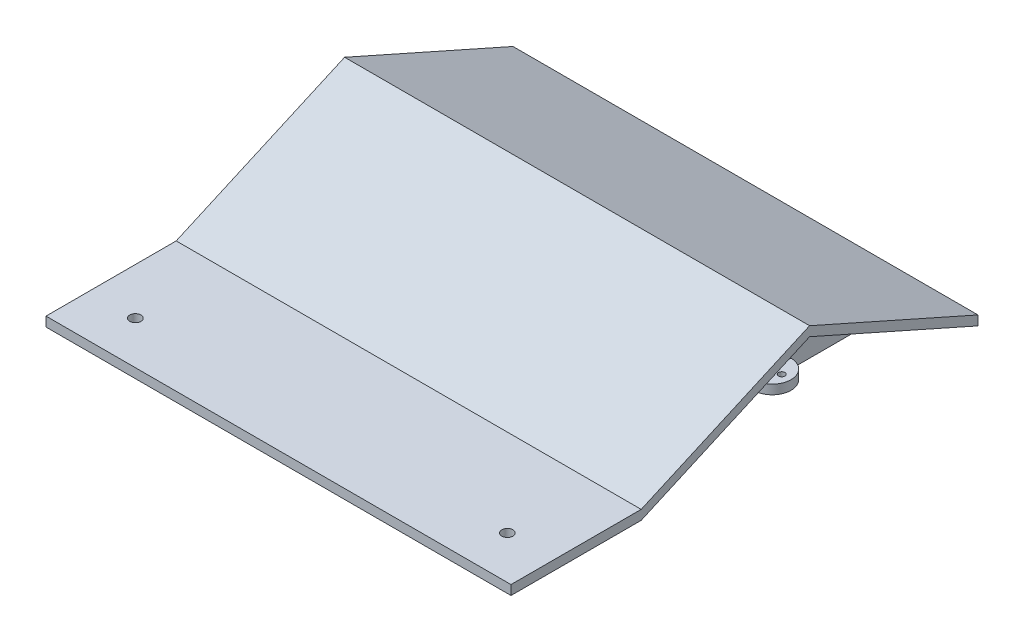
SolidWorks part; units mm, degrees
ref_plane "Front Plane" through (0, 0, 0) normal (0, 0, 1) x (1, 0, 0)
ref_plane "Top Plane" through (0, 0, 0) normal (0, 1, 0) x (1, 0, 0)
ref_plane "Right Plane" through (0, 0, 0) normal (1, 0, 0) x (0, 0, -1)
sketch "Sketch1" plane through (0, 0, 0) normal (1, 0, 0) x (0, 0, -1)
  line L0 (0, 0) -> (135, 0)
  line L1 (67.5, 0) -> (67.5, 30)
  line L2 (67.5, 30) -> (135, 0)
  line L3 (135, 0) -> (158.0421, -10.2409)
  line L4 (158.0421, -10.2409) -> (158.0421, -5.1205)
  line L5 (158.0421, -5.1205) -> (67.5, 35.1205)
  line L6 (67.5, 30) -> (0, 0)
  line L7 (0, 0) -> (-23.0421, -10.2409)
  line L8 (-23.0421, -10.2409) -> (-23.0421, -5.1205)
  line L9 (-23.0421, -5.1205) -> (67.5, 35.1205)
extrude "Boss-Extrude1" add sketch "Sketch1" against normal blind 250 contours L9 L8 L7 L6 L2 L3 L4 L5
sketch "Sketch2" plane through (0, 0, 0) normal (1, 0, 0) x (0, 0, -1)
  line L0 (0, 0) -> (135, 0)
  line L1 (67.5, 30) -> (158.0421, -10.2409) construction
  line L2 (135, 0) -> (67.5, 30)
  line L3 (67.5, 30) -> (0, 0)
extrude "Boss-Extrude2" add sketch "Sketch2" against normal blind 25
sketch "Sketch3" plane through (0, 0, 0) normal (1, 0, 0) x (0, 0, -1)
  line L0 (0, 0) -> (135, 0)
  line L1 (135, 0) -> (67.5, 30)
  line L2 (67.5, 30) -> (0, 0)
extrude "Cut-Extrude1" cut sketch "Sketch3" against normal blind 20
sketch "Sketch4" plane through (-250, 0, 0) normal (-1, 0, 0) x (0, 0, 1)
  line L0 (-135, 0) -> (0, 0)
  line L1 (0, 0) -> (-67.5, 30)
  line L2 (-67.5, 30) -> (-135, 0)
extrude "Boss-Extrude3" add sketch "Sketch4" against normal blind 25
sketch "Sketch5" plane through (-250, 0, 0) normal (-1, 0, 0) x (0, 0, 1)
  line L0 (-135, 0) -> (0, 0)
  line L1 (0, 0) -> (-67.5, 29.5827)
  line L2 (-67.5, 29.5827) -> (-135, 0)
extrude "Cut-Extrude2" cut sketch "Sketch5" against normal blind 20
sketch "Sketch6" plane through (0, 0, 0) normal (0, -1, 0) x (-1, 0, 0)
  line L0 (230, 67.5) -> (240, 67.5)
  circle A0 centre (230, 67.5) radius 10
  circle A1 centre (235, 67.5) radius 1.7
  line M1 (230, 0) -> (230, 135)
  line M3 (225, 135) -> (225, 0)
extrude "Boss-Extrude4" add sketch "Sketch6" against normal blind 5 contours A1 L0 A0 M1 | A1 L0 A0 M1 | A0 M3 | A0 M1 M3
sketch "Sketch7" plane through (0, 0, 0) normal (0, -1, 0) x (-1, 0, 0)
  line L0 (20, 67.5) -> (10, 67.5)
  circle A0 centre (20, 67.5) radius 10
  circle A1 centre (15, 67.5) radius 1.7
  line M1 (20, 135) -> (20, 0)
  line M3 (25, 0) -> (25, 135)
extrude "Boss-Extrude5" add sketch "Sketch7" against normal blind 5 contours A1 L0 A0 M1 | A1 L0 A0 M1 | A0 M1 M3 | A0 M3
sketch "Sketch8" plane through (-230, 0, 0) normal (-1, 0, 0) x (0, 0, 1)
  line L0 (-67.5, 5) -> (-67.5, 25)
  line L1 (-57.5, 5) -> (-77.5, 5) construction
  circle A0 centre (-67.5, 25) radius 1.5
extrude "Cut-Extrude3" cut sketch "Sketch8" against normal blind 10
sketch "Sketch9" plane through (-250, 0, 0) normal (-1, 0, 0) x (0, 0, 1)
  line L0 (23.0421, -5.1205) -> (93.0421, -5.1205)
  line L1 (93.0421, -5.1205) -> (93.0421, -10.2409)
  line L2 (93.0421, -10.2409) -> (23.0421, -10.2409)
  line L3 (23.0421, -10.2409) -> (23.0421, -5.1205)
extrude "Boss-Extrude7" add sketch "Sketch9" against normal blind 250
sketch "Sketch10" plane through (-250, 0, 0) normal (-1, 0, 0) x (0, 0, 1)
  line L0 (0, 0) -> (0, 5.1205)
  line L1 (23.0421, -5.1205) -> (-67.5, 35.1205) construction
  line L2 (0, 5.1205) -> (70, 5.1205)
  line L3 (70, 5.1205) -> (70, -5.1205)
  line L4 (93.0421, -5.1205) -> (23.0421, -5.1205) construction
sketch "Sketch11" plane through (0, -5.1205, 0) normal (0, 1, 0) x (1, 0, 0)
  line L0 (-250, -70) -> (-225, -70)
  line L1 (-250, 0) -> (-250, -70) construction
  line L2 (-250, -93.0421) -> (-250, -23.0421) construction
  line L3 (0, -70) -> (-25, -70)
  line L4 (0, -93.0421) -> (0, -23.0421) construction
  circle A0 centre (-225, -70) radius 3
  circle A1 centre (-25, -70) radius 3
extrude "Cut-Extrude4" cut sketch "Sketch11" against normal blind 90
